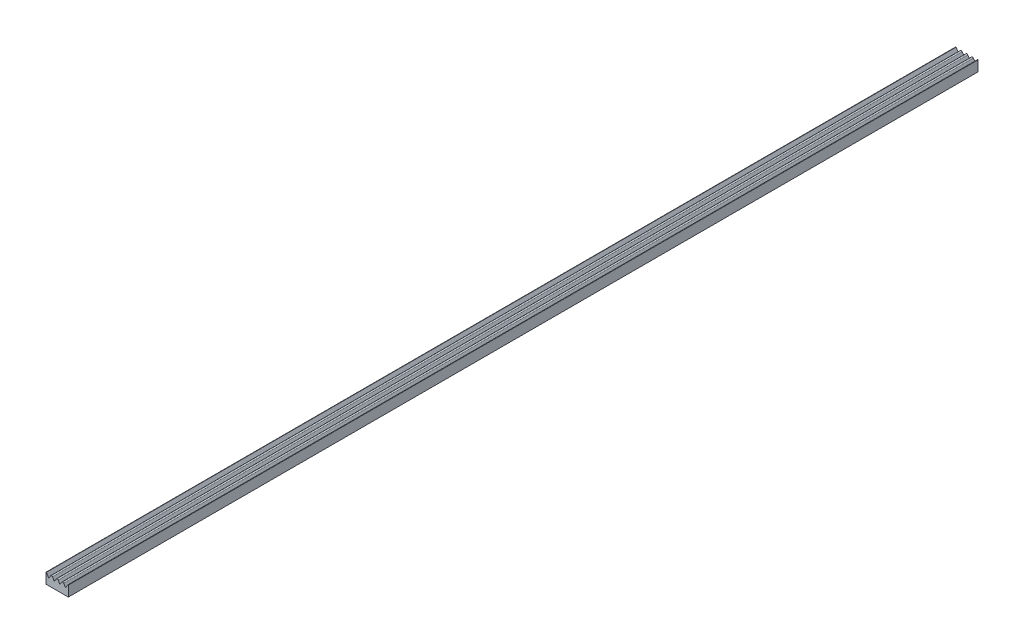
SolidWorks part; units mm, degrees
material "Polyurethane Foam Flexible"
ref_plane "Front Plane" through (0, 0, 0) normal (0, 0, 1) x (1, 0, 0)
ref_plane "Top Plane" through (0, 0, 0) normal (0, 1, 0) x (1, 0, 0)
ref_plane "Right Plane" through (0, 0, 0) normal (1, 0, 0) x (0, 0, -1)
sketch "Sketch1" plane through (0, 0, 0) normal (0, 0, 1) x (1, 0, 0)
  line L0 (-12.7, 6.35) -> (0, 6.35) construction
  line L1 (0, 0) -> (-12.7, 0)
  line L2 (0, 0) -> (0, 5.9072)
  line L3 (-6.35, 0) -> (-6.35, 6.35) construction
  line L4 (-12.7, 0) -> (-12.7, 5.9072)
  line L5 (-12.7, 3.81) -> (0, 3.81) construction
  line L6 (-7.9375, 3.81) -> (-6.8885, 5.4884)
  line L7 (-7.9375, 3.81) -> (-8.9865, 5.4884)
  line L8 (-10.0635, 5.4884) -> (-11.1125, 3.81)
  line L9 (-11.1125, 3.81) -> (-12.4653, 5.9745)
  line L10 (-4.7625, 3.81) -> (-5.8115, 5.4884)
  line L11 (-4.7625, 3.81) -> (-3.7135, 5.4884)
  line L14 (-2.6365, 5.4884) -> (-1.5875, 3.81)
  line L15 (-1.5875, 3.81) -> (-0.2347, 5.9745)
  arc A0 (-3.7135, 5.4884) -> (-2.6365, 5.4884) centre (-3.175, 5.1519) cw
  arc A1 (-6.8885, 5.4884) -> (-5.8115, 5.4884) centre (-6.35, 5.1519) cw
  arc A2 (-8.9865, 5.4884) -> (-10.0635, 5.4884) centre (-9.525, 5.1519) ccw
  arc A3 (0, 5.9072) -> (-0.2347, 5.9745) centre (-0.127, 5.9072) ccw
  arc A4 (-12.4653, 5.9745) -> (-12.7, 5.9072) centre (-12.573, 5.9072) ccw
  dimension "D7" = 0.635
  dimension "D8" = 0.127
  dimension "D1" = 6.35
  dimension "D2" = 12.7
  dimension "D3" = 1.5875
  dimension "D4" = 2.54
  dimension "D5" = 1.5875
extrude "Boss-Extrude1" add sketch "Sketch1" along normal blind 517.525
